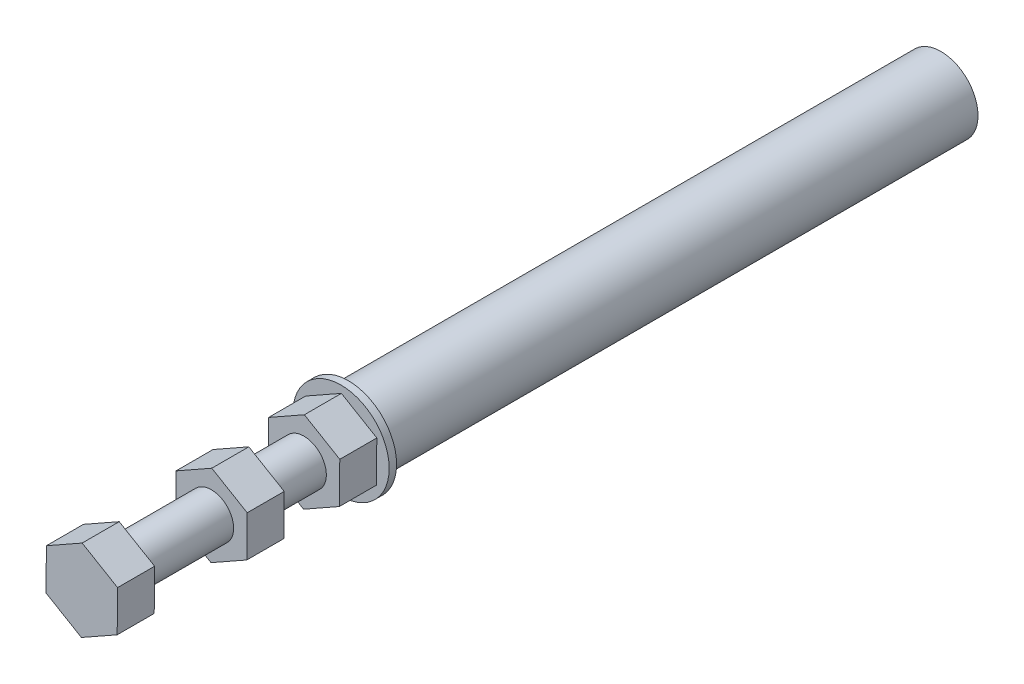
SolidWorks part; units mm, degrees
ref_plane "Front Plane" through (0, 0, 0) normal (0, 0, 1) x (1, 0, 0)
ref_plane "Top Plane" through (0, 0, 0) normal (0, 1, 0) x (1, 0, 0)
ref_plane "Right Plane" through (0, 0, 0) normal (1, 0, 0) x (0, 0, -1)
sketch "Sketch1" plane through (0, 0, 0) normal (0, 0, 1) x (1, 0, 0)
  circle A0 centre (0, 0) radius 5
  dimension "D1" = 10
extrude "Boss-Extrude1" add sketch "Sketch1" along normal blind 80
sketch "Sketch2" plane through (0, 0, 80) normal (0, 0, 1) x (1, 0, 0)
  circle A0 centre (0, 0) radius 6.5
  dimension "D1" = 13
extrude "Boss-Extrude2" add sketch "Sketch2" along normal blind 1
sketch "Sketch5" plane through (0, 0, 81) normal (0, 0, 1) x (1, 0, 0)
  line L1 (4.7789, -2.8202) -> (4.8318, 2.7285)
  line L2 (4.8318, 2.7285) -> (0.0529, 5.5487)
  line L3 (0.0529, 5.5487) -> (-4.7789, 2.8202)
  line L4 (-4.7789, 2.8202) -> (-4.8318, -2.7285)
  line L5 (-4.8318, -2.7285) -> (-0.0529, -5.5487)
  line L6 (-0.0529, -5.5487) -> (4.7789, -2.8202)
  circle A0 centre (0, 0) radius 4.8055 construction
extrude "Boss-Extrude5" add sketch "Sketch5" along normal blind 5
sketch "Sketch6" plane through (0, 0, 86) normal (0, 0, 1) x (1, 0, 0)
  circle A0 centre (0, 0) radius 3.0197
  dimension "D1" = 6.0393
extrude "Boss-Extrude6" add sketch "Sketch6" along normal blind 7.5
sketch "Sketch7" plane through (0, 0, 93.5) normal (0, 0, 1) x (1, 0, 0)
  line L1 (4.7789, -2.8202) -> (4.8318, 2.7285)
  line L2 (4.8318, 2.7285) -> (0.0529, 5.5487)
  line L3 (0.0529, 5.5487) -> (-4.7789, 2.8202)
  line L4 (-4.7789, 2.8202) -> (-4.8318, -2.7285)
  line L5 (-4.8318, -2.7285) -> (-0.0529, -5.5487)
  line L6 (-0.0529, -5.5487) -> (4.7789, -2.8202)
  circle A0 centre (0, 0) radius 4.8055 construction
extrude "Boss-Extrude7" add sketch "Sketch7" along normal blind 5
sketch "Sketch8" plane through (0, 0, 98.5) normal (0, 0, 1) x (1, 0, 0)
  circle A0 centre (0, 0) radius 3
  dimension "D1" = 6
extrude "Boss-Extrude8" add sketch "Sketch8" along normal blind 12.5
sketch "Sketch9" plane through (0, 0, 111) normal (0, 0, 1) x (1, 0, 0)
  line L1 (4.7789, -2.8202) -> (4.8318, 2.7285)
  line L2 (4.8318, 2.7285) -> (0.0529, 5.5487)
  line L3 (0.0529, 5.5487) -> (-4.7789, 2.8202)
  line L4 (-4.7789, 2.8202) -> (-4.8318, -2.7285)
  line L5 (-4.8318, -2.7285) -> (-0.0529, -5.5487)
  line L6 (-0.0529, -5.5487) -> (4.7789, -2.8202)
  circle A0 centre (0, 0) radius 4.8055 construction
extrude "Boss-Extrude9" add sketch "Sketch9" along normal blind 5
